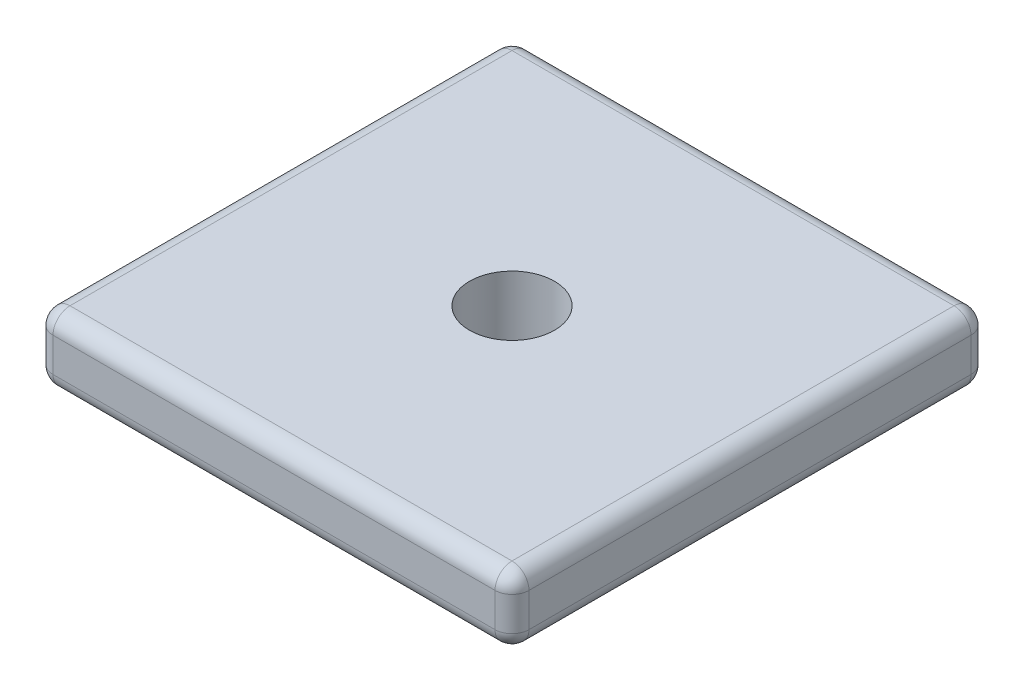
SolidWorks part; units mm, degrees
ref_plane "Front Plane" through (0, 0, 0) normal (0, 0, 1) x (1, 0, 0)
ref_plane "Top Plane" through (0, 0, 0) normal (0, 1, 0) x (1, 0, 0)
ref_plane "Right Plane" through (0, 0, 0) normal (1, 0, 0) x (0, 0, -1)
sketch "Sketch1" plane through (0, 0, 0) normal (0, 1, 0) x (1, 0, 0)
  line L1 (-70.1667, 56) -> (-84.1667, 56)
  line L2 (-70.1667, 56) -> (-70.1667, 70)
  line L3 (-70.1667, 70) -> (-84.1667, 70)
  line L4 (-84.1667, 56) -> (-84.1667, 70)
  point P0 (0, 0)
  dimension "D1" = 14
  dimension "D2" = 14
extrude "Boss-Extrude1" add sketch "Sketch1" along normal blind 2
fillet "Fillet1" radius 0.5 12 edges at (-84.1667, 1, -70) (-77.1667, 0, -70) (-84.1667, 0, -63) (-84.1667, 1, -56) (-77.1667, 0, -56) (-77.1667, 2, -70) (-77.1667, 2, -56) (-84.1667, 2, -63) (-70.1667, 1, -56) (-70.1667, 2, -63) (-70.1667, 1, -70) (-70.1667, 0, -63)
sketch "Sketch2" plane through (0, 2, 0) normal (0, 1, 0) x (1, 0, 0)
  circle A1 centre (-77.1667, 63) radius 1.25
extrude "Cut-Extrude1" cut sketch "Sketch2" against normal blind 2 contours A1
